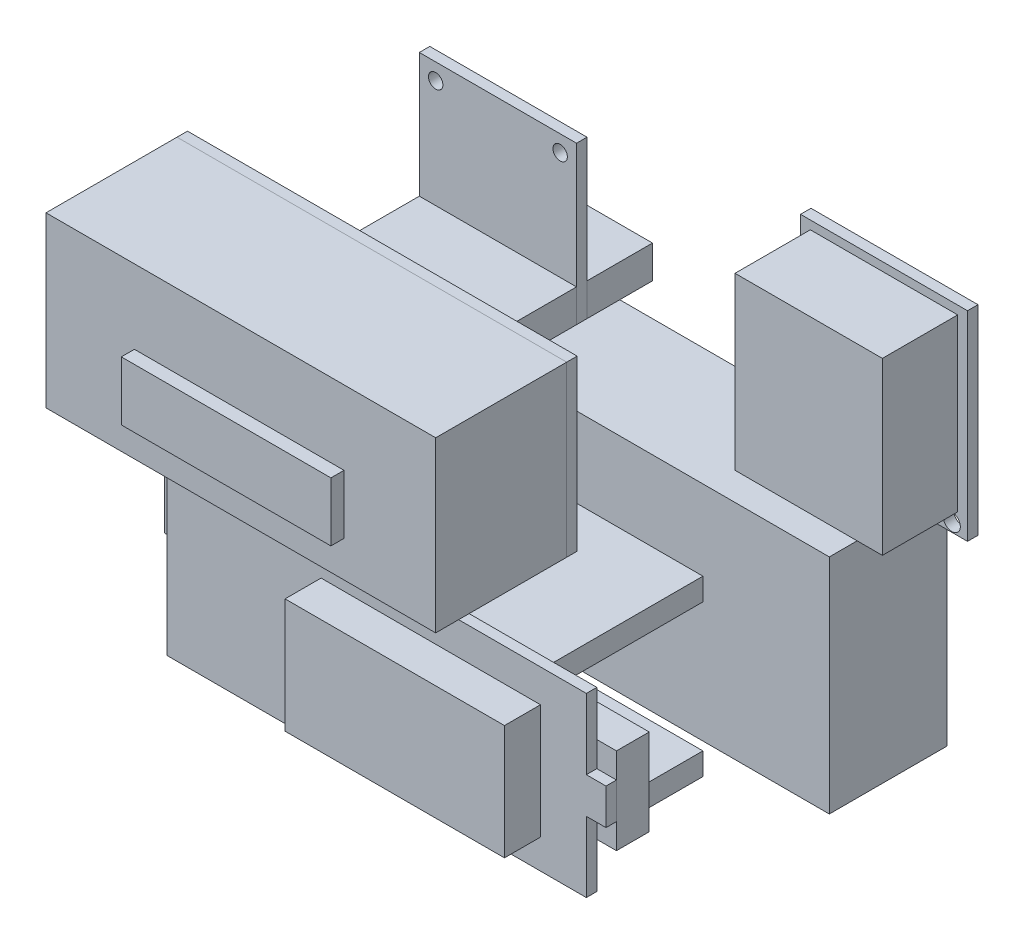
SolidWorks part; units mm, degrees
ref_plane "前视基准面" through (0, 0, 0) normal (0, 0, 1) x (1, 0, 0)
ref_plane "上视基准面" through (0, 0, 0) normal (0, 1, 0) x (1, 0, 0)
ref_plane "右视基准面" through (0, 0, 0) normal (1, 0, 0) x (0, 0, -1)
other "Configuration Table"
sketch "电池盒 profile" plane through (0, 0, 0) normal (0, 0, 1) x (1, 0, 0)
  line L0 (-34.5, -33) -> (34.5, -33)
  line L1 (34.5, -33) -> (34.5, 1)
  line L2 (34.5, 1) -> (-34.5, 1)
  line L3 (-34.5, 1) -> (-34.5, -33)
extrude "电池盒" add sketch "电池盒 profile" along normal blind 18 from offset 4 separate body
sketch "传感器板 24×24，Ø2.2孔 profile" plane through (0, 0, 0) normal (0, 0, 1) x (1, 0, 0)
  line L0 (-34.5, 6) -> (-10.5, 6)
  line L1 (-10.5, 6) -> (-10.5, 30)
  line L2 (-10.5, 30) -> (-34.5, 30)
  line L3 (-34.5, 30) -> (-34.5, 6)
  circle A0 centre (-32, 27.5) radius 1.1
  circle A1 centre (-13, 27.5) radius 1.1
extrude "传感器板 24×24，Ø2.2孔" add sketch "传感器板 24×24，Ø2.2孔 profile" along normal blind 1.6 from offset 14 separate body
sketch "排针侧5mm，板下按10mm避空 profile" plane through (0, 0, 0) normal (0, 0, 1) x (1, 0, 0)
  line L0 (-34.5, 6) -> (-10.5, 6)
  line L1 (-10.5, 6) -> (-10.5, 11)
  line L2 (-10.5, 11) -> (-34.5, 11)
  line L3 (-34.5, 11) -> (-34.5, 6)
extrude "排针侧5mm，板下按10mm避空" add sketch "排针侧5mm，板下按10mm避空 profile" along normal blind 10 from offset 4 separate body
sketch "排针侧5mm，板上线头和弯线预留 profile" plane through (0, 0, 0) normal (0, 0, 1) x (1, 0, 0)
  line L0 (-34.5, 6) -> (-10.5, 6)
  line L1 (-10.5, 6) -> (-10.5, 11)
  line L2 (-10.5, 11) -> (-34.5, 11)
  line L3 (-34.5, 11) -> (-34.5, 6)
extrude "排针侧5mm，板上线头和弯线预留" add sketch "排针侧5mm，板上线头和弯线预留 profile" along normal blind 23 from offset 15.6 separate body
sketch "GNSS板，3mm单边Ø2.6安装区 profile" plane through (0, 0, 0) normal (0, 0, 1) x (1, 0, 0)
  line L0 (18.5, 2) -> (44, 2)
  line L1 (44, 2) -> (44, 32.5)
  line L2 (44, 32.5) -> (18.5, 32.5)
  line L3 (18.5, 32.5) -> (18.5, 2)
  circle A0 centre (21.1, 3.4) radius 1.3
  circle A1 centre (41.6, 3.4) radius 1.3
extrude "GNSS板，3mm单边Ø2.6安装区" add sketch "GNSS板，3mm单边Ø2.6安装区 profile" along normal blind 1.6 from offset 8.8 separate body
sketch "GNSS陶瓷天线面朝上，保留11.5mm profile" plane through (0, 0, 0) normal (0, 0, 1) x (1, 0, 0)
  line L0 (20, 5.15) -> (42.5, 5.15)
  line L1 (42.5, 5.15) -> (42.5, 31.2)
  line L2 (42.5, 31.2) -> (20, 31.2)
  line L3 (20, 31.2) -> (20, 5.15)
extrude "GNSS陶瓷天线面朝上，保留11.5mm" add sketch "GNSS陶瓷天线面朝上，保留11.5mm profile" along normal blind 11.5 from offset 10.4 separate body
sketch "GNSS背面插头预留 profile" plane through (0, 0, 0) normal (0, 0, 1) x (1, 0, 0)
  line L0 (26, 2.05) -> (34, 2.05)
  line L1 (34, 2.05) -> (34, 8.5)
  line L2 (34, 8.5) -> (26, 8.5)
  line L3 (26, 8.5) -> (26, 2.05)
extrude "GNSS背面插头预留" add sketch "GNSS背面插头预留 profile" along normal blind 4.5 from offset 4.3 separate body
sketch "电源板正面朝上 profile" plane through (0, 0, 0) normal (0, 0, 1) x (1, 0, 0)
  line L0 (-41.5, 4.5) -> (18, 4.5)
  line L1 (18, 4.5) -> (18, 30.3)
  line L2 (18, 30.3) -> (-41.5, 30.3)
  line L3 (-41.5, 30.3) -> (-41.5, 4.5)
  circle A0 centre (-36.75, 8.9) radius 1.5
  circle A1 centre (13.25, 8.9) radius 1.5
  circle A2 centre (-36.75, 25.9) radius 1.5
  circle A3 centre (13.25, 25.9) radius 1.5
extrude "电源板正面朝上" add sketch "电源板正面朝上 profile" along normal blind 1.6 from offset 44 separate body
sketch "电源板最高件20mm净空 profile" plane through (0, 0, 0) normal (0, 0, 1) x (1, 0, 0)
  line L0 (-41.5, 4.5) -> (18, 4.5)
  line L1 (18, 4.5) -> (18, 30.3)
  line L2 (18, 30.3) -> (-41.5, 30.3)
  line L3 (-41.5, 30.3) -> (-41.5, 4.5)
extrude "电源板最高件20mm净空" add sketch "电源板最高件20mm净空 profile" along normal blind 20 from offset 45.6 separate body
sketch "电源板插线预留超过20mm的部分 profile" plane through (0, 0, 0) normal (0, 0, 1) x (1, 0, 0)
  line L0 (-28, 10) -> (4, 10)
  line L1 (4, 10) -> (4, 19)
  line L2 (4, 19) -> (-28, 19)
  line L3 (-28, 19) -> (-28, 10)
extrude "电源板插线预留超过20mm的部分" add sketch "电源板插线预留超过20mm的部分 profile" along normal blind 2 from offset 65.6 separate body
sketch "EoRa屏幕面朝上的开发板及端部凸起 profile" plane through (0, 0, 0) normal (0, 0, 1) x (1, 0, 0)
  line L0 (-32, -28) -> (32, -28)
  line L1 (32, -28) -> (32, -17.25)
  line L2 (32, -17.25) -> (35, -17.25)
  line L3 (35, -17.25) -> (35, -11.75)
  line L4 (35, -11.75) -> (32, -11.75)
  line L5 (32, -11.75) -> (32, -1)
  line L6 (32, -1) -> (-32, -1)
  line L7 (-32, -1) -> (-32, -28)
extrude "EoRa屏幕面朝上的开发板及端部凸起" add sketch "EoRa屏幕面朝上的开发板及端部凸起 profile" along normal blind 1.6 from offset 55 separate body
sketch "EoRa屏幕5.5mm profile" plane through (0, 0, 0) normal (0, 0, 1) x (1, 0, 0)
  line L0 (-8.5, -23.5) -> (25, -23.5)
  line L1 (25, -23.5) -> (25, -6)
  line L2 (25, -6) -> (-8.5, -6)
  line L3 (-8.5, -6) -> (-8.5, -23.5)
extrude "EoRa屏幕5.5mm" add sketch "EoRa屏幕5.5mm profile" along normal blind 5.5 from offset 56.6 separate body
sketch "EoRa背面排针和杜邦线通道甲 profile" plane through (0, 0, 0) normal (0, 0, 1) x (1, 0, 0)
  line L0 (-10.5, -27.7) -> (25.2, -27.7)
  line L1 (25.2, -27.7) -> (25.2, -24.3)
  line L2 (25.2, -24.3) -> (-10.5, -24.3)
  line L3 (-10.5, -24.3) -> (-10.5, -27.7)
extrude "EoRa背面排针和杜邦线通道甲" add sketch "EoRa背面排针和杜邦线通道甲 profile" along normal blind 23 from offset 32 separate body
sketch "EoRa背面排针和杜邦线通道乙 profile" plane through (0, 0, 0) normal (0, 0, 1) x (1, 0, 0)
  line L0 (-10.5, -4.6) -> (25.2, -4.6)
  line L1 (25.2, -4.6) -> (25.2, -1.2)
  line L2 (25.2, -1.2) -> (-10.5, -1.2)
  line L3 (-10.5, -1.2) -> (-10.5, -4.6)
extrude "EoRa背面排针和杜邦线通道乙" add sketch "EoRa背面排针和杜邦线通道乙 profile" along normal blind 23 from offset 32 separate body
sketch "EoRa接口端背面4mm避空 profile" plane through (0, 0, 0) normal (0, 0, 1) x (1, 0, 0)
  line L0 (-34, -13.6) -> (-27, -13.6)
  line L1 (-27, -13.6) -> (-27, -4.3)
  line L2 (-27, -4.3) -> (-34, -4.3)
  line L3 (-34, -4.3) -> (-34, -13.6)
extrude "EoRa接口端背面4mm避空" add sketch "EoRa接口端背面4mm避空 profile" along normal blind 4 from offset 51 separate body
sketch "EoRa另一端背面5mm避空 profile" plane through (0, 0, 0) normal (0, 0, 1) x (1, 0, 0)
  line L0 (27, -21.1) -> (35, -21.1)
  line L1 (35, -21.1) -> (35, -7.9)
  line L2 (35, -7.9) -> (27, -7.9)
  line L3 (27, -7.9) -> (27, -21.1)
extrude "EoRa另一端背面5mm避空" add sketch "EoRa另一端背面5mm避空 profile" along normal blind 5 from offset 50 separate body
